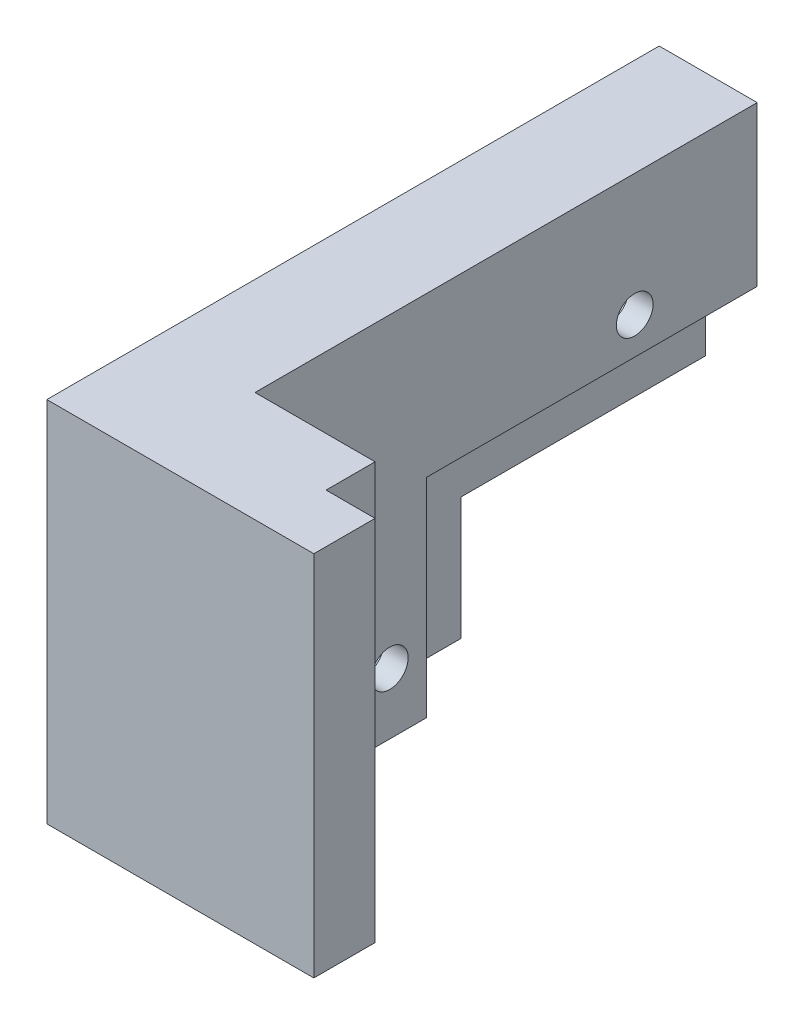
SolidWorks part; units mm, degrees
ref_plane "前视基准面" through (0, 0, 0) normal (0, 0, 1) x (1, 0, 0)
ref_plane "上视基准面" through (0, 0, 0) normal (0, 1, 0) x (1, 0, 0)
ref_plane "右视基准面" through (0, 0, 0) normal (1, 0, 0) x (0, 0, -1)
other "Configuration Table"
sketch "草图1" plane through (0, 0, 0) normal (0, 0, 1) x (1, 0, 0)
  line L1 (0, 0) -> (-40, 0)
  line L2 (0, 0) -> (0, 30)
  line L3 (0, 30) -> (-40, 30)
  line L4 (-40, 0) -> (-40, 30)
  dimension "D1" = 40
  dimension "D2" = 30
extrude "凸台-拉伸1" add sketch "草图1" along normal blind 5
sketch "草图2" plane through (-40, 0, 0) normal (-1, 0, 0) x (0, 0, 1)
  line L4 (0, 30) -> (0, 0)
  line L5 (0, 0) -> (5, 0)
  line L6 (5, 0) -> (5, 30)
  line L7 (5, 30) -> (0, 30)
  line L8 (0, 30) -> (0, 0)
  line L9 (0, 0) -> (5, 0)
  line L10 (5, 0) -> (5, 30)
  line L11 (5, 30) -> (0, 30)
  dimension "D1" = 0
extrude "凸台-拉伸2" add sketch "草图2" along normal blind 20
sketch "草图3" plane through (0, 0, 0) normal (0, 0, -1) x (-1, 0, 0)
  line L0 (60, 0) -> (0, 0) construction
  line L1 (60, 30) -> (40, 30)
  line L2 (60, 30) -> (60, 0)
  line L3 (60, 0) -> (40, 0)
  line L4 (40, 30) -> (40, 0)
  dimension "D1" = 20
extrude "凸台-拉伸3" add sketch "草图3" along normal blind 5
sketch "草图4" plane through (0, 0, 5) normal (0, 0, 1) x (1, 0, 0)
  line L0 (0, 30) -> (-60, 30) construction
  line L1 (-60, 30) -> (-45, 30)
  line L2 (-60, 30) -> (-60, 0)
  line L3 (-60, 0) -> (-45, 0)
  line L4 (-45, 30) -> (-45, 0)
  line L5 (-60, 0) -> (0, 0) construction
  line L6 (-60, 0) -> (-60, 30) construction
  dimension "D1" = 0
  dimension "D2" = 15
extrude "切除-拉伸1" cut sketch "草图4" against normal blind 5
sketch "草图5" plane through (0, 0, 0) normal (0, 0, 1) x (1, 0, 0)
  line L0 (-52.5, 30) -> (-52.5, 25) construction
  line L1 (-45, 30) -> (-60, 30) construction
  line L2 (-52.5, 25) -> (-52.5, 5) construction
  circle A0 centre (-52.5, 5) radius 1.5
  circle A1 centre (-52.5, 25) radius 1.5
  dimension "D3" = 3
  dimension "D4" = 3
  dimension "D1" = 5
  dimension "D2" = 20
extrude "切除-拉伸2" cut sketch "草图5" against normal blind 5
sketch "草图6" plane through (0, 0, 0) normal (0, 0, 1) x (1, 0, 0)
  circle A0 centre (-52.5, 25) radius 3
  circle A1 centre (-52.5, 5) radius 3
  dimension "D1" = 6
  dimension "D2" = 6
extrude "切除-拉伸3" cut sketch "草图6" against normal blind 2
sketch "草图7" plane through (0, 0, 0) normal (0, 0, 1) x (1, 0, 0)
  line L4 (-60, 30) -> (-60, 0)
  line L5 (-60, 0) -> (-45, 0)
  line L6 (-45, 0) -> (-45, 30)
  line L7 (-45, 30) -> (-60, 30)
  line L8 (-60, 30) -> (-60, 0)
  line L9 (-60, 0) -> (-45, 0)
  line L10 (-45, 0) -> (-45, 30)
  line L11 (-45, 30) -> (-60, 30)
  dimension "D1" = 0
extrude "切除-拉伸4" cut sketch "草图7" against normal blind 10
sketch "草图8" plane through (0, 0, -5) normal (0, 0, -1) x (-1, 0, 0)
  line L4 (40, 0) -> (45, 0)
  line L5 (45, 0) -> (45, 30)
  line L6 (45, 30) -> (40, 30)
  line L7 (40, 30) -> (40, 0)
  line L8 (40, 0) -> (45, 0)
  line L9 (45, 0) -> (45, 30)
  line L10 (45, 30) -> (40, 30)
  line L11 (40, 30) -> (40, 0)
  dimension "D1" = 0
extrude "凸台-拉伸4" add sketch "草图8" along normal blind 20
sketch "草图9" plane through (-40, 0, 0) normal (1, 0, 0) x (0, 0, -1)
  line L0 (25, 0) -> (0, 0) construction
  line L1 (25, 30) -> (18, 30)
  line L2 (25, 30) -> (25, 0)
  line L3 (25, 0) -> (18, 0)
  line L4 (18, 30) -> (18, 0)
  dimension "D1" = 7
sketch "草图10" plane through (-45, 0, 0) normal (-1, 0, 0) x (0, 0, 1)
  line L4 (5, 0) -> (5, 30)
  line L5 (5, 30) -> (-25, 30)
  line L6 (-25, 30) -> (-25, 0)
  line L7 (-25, 0) -> (5, 0)
  line L8 (5, 0) -> (5, 30)
  line L9 (5, 30) -> (-25, 30)
  line L10 (-25, 30) -> (-25, 0)
  line L11 (-25, 0) -> (5, 0)
  dimension "D1" = 0
extrude "凸台-拉伸5" add sketch "草图10" along normal blind 3
sketch "草图11" plane through (-48, 0, 0) normal (-1, 0, 0) x (0, 0, 1)
  line L0 (-25, 30) -> (-15, 30) construction
  line L1 (5, 30) -> (-25, 30) construction
  line L2 (-15, 30) -> (-15, 5) construction
  circle A0 centre (-15, 5) radius 1.5
  dimension "D4" = 3
  dimension "D1" = 25
  dimension "D3" = 10
extrude "切除-拉伸6" cut sketch "草图11" against normal blind 13
sketch "草图12" plane through (-48, 0, 0) normal (-1, 0, 0) x (0, 0, 1)
  circle A0 centre (-15, 5) radius 2.9
  dimension "D1" = 5.8
extrude "切除-拉伸7" cut sketch "草图12" against normal offset from surface (6 mm away) 2 up to face at (-40, 5, -13.5)
sketch "草图14" plane through (0, 0, -25) normal (0, 0, -1) x (-1, 0, 0)
  line L0 (40, 30) -> (40, 0) construction
  line L1 (48, 30) -> (40, 30)
  line L2 (48, 30) -> (48, 10)
  line L3 (48, 10) -> (40, 10)
  line L4 (40, 30) -> (40, 10)
  dimension "D1" = 20
extrude "凸台-拉伸6" add sketch "草图14" along normal blind 20
sketch "草图15" plane through (-40, 0, 0) normal (1, 0, 0) x (0, 0, -1)
  line L1 (45, 10) -> (25, 10)
  line L2 (45, 10) -> (45, 17)
  line L3 (45, 17) -> (18, 17)
  line L4 (18, 10) -> (18, 17)
  line L6 (18, 10) -> (18, 0)
  line L7 (18, 0) -> (25, 0)
  line L8 (25, 10) -> (25, 0)
  dimension "D1" = 7
  dimension "D2" = 7
extrude "切除-拉伸8" cut sketch "草图15" against normal blind 4.2
sketch "草图16" plane through (-48, 0, 0) normal (-1, 0, 0) x (0, 0, 1)
  line L0 (-45, 30) -> (-45, 20) construction
  line L1 (-45, 10) -> (-45, 30) construction
  line L2 (-45, 20) -> (-35, 20) construction
  circle A0 centre (-35, 20) radius 1.5
  dimension "D3" = 3
  dimension "D1" = 10
  dimension "D2" = 10
extrude "切除-拉伸9" cut sketch "草图16" against normal blind 14.2
sketch "草图17" plane through (-48, 0, 0) normal (-1, 0, 0) x (0, 0, 1)
  circle A0 centre (-35, 20) radius 2.9
  dimension "D1" = 5.8
extrude "切除-拉伸10" cut sketch "草图17" against normal offset from surface (6 mm away) 2 up to face at (-40, 20, -33.5)
sketch "草图18" plane through (-40, 0, 0) normal (1, 0, 0) x (0, 0, -1)
  line L0 (18, 0) -> (0, 0) construction
  line L1 (0, 30) -> (4, 30)
  line L2 (0, 30) -> (0, 0)
  line L3 (0, 0) -> (4, 0)
  line L4 (4, 30) -> (4, 0)
  dimension "D1" = 4
extrude "凸台-拉伸7" add sketch "草图18" along normal blind 9.8
sketch "草图19" plane through (0, 0, 0) normal (1, 0, 0) x (0, 0, -1)
  line L4 (0, 0) -> (0, 30)
  line L5 (0, 30) -> (-5, 30)
  line L6 (-5, 30) -> (-5, 0)
  line L7 (-5, 0) -> (0, 0)
  line L8 (0, 0) -> (0, 30)
  line L9 (0, 30) -> (-5, 30)
  line L10 (-5, 30) -> (-5, 0)
  line L11 (-5, 0) -> (0, 0)
  dimension "D1" = 0
extrude "切除-拉伸11" cut sketch "草图19" against normal offset from surface (26.2 mm away) 4 up to face at (-30.2, 15, -2)
